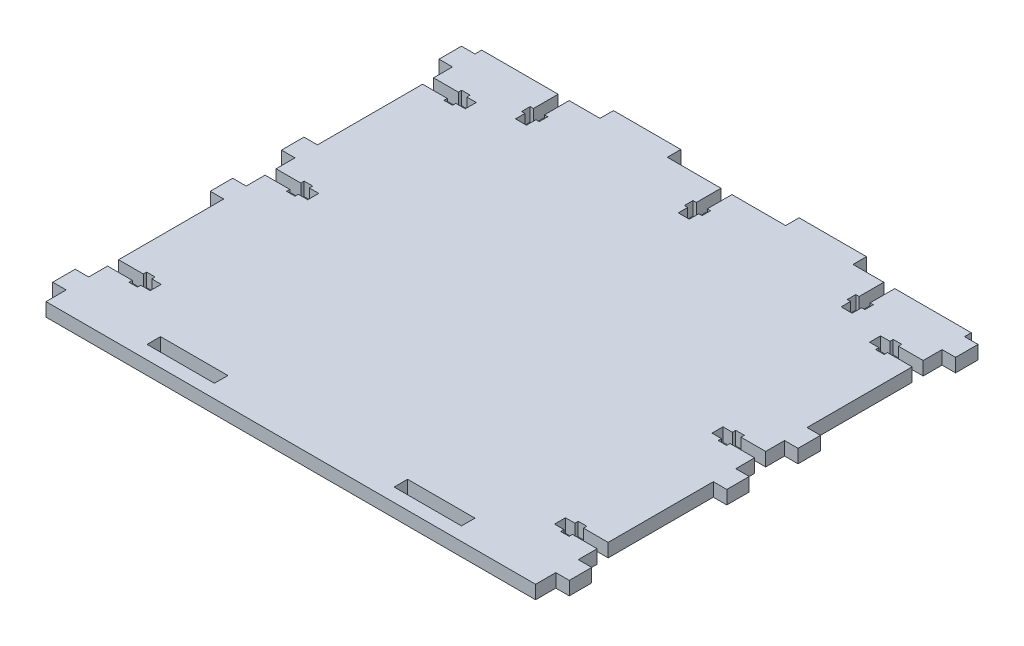
SolidWorks part; units mm, degrees
ref_plane "Спереди" through (0, 0, 0) normal (0, 0, 1) x (1, 0, 0)
ref_plane "Сверху" through (0, 0, 0) normal (0, 1, 0) x (1, 0, 0)
ref_plane "Справа" through (0, 0, 0) normal (1, 0, 0) x (0, 0, -1)
sketch "Эскиз1" plane through (0, 0, 0) normal (0, 1, 0) x (1, 0, 0)
  line L0 (0, 0) -> (0, 50000) construction
  line L1 (0, 0) -> (50000, 0) construction
  line L2 (-44.5, 88.435) -> (44.5, 88.435) construction
  line L3 (-44.5, -88.435) -> (44.5, -88.435) construction
  line L4 (26.3333, 100) -> (26.3333, 94)
  line L5 (115, -100) -> (-115, -100) construction
  line L6 (115, -100) -> (115, 100) construction
  line L7 (115, 100) -> (-115, 100) construction
  line L8 (-115, -100) -> (-115, 100) construction
  line L9 (115, -100) -> (-115, 100) construction
  line L10 (115, 100) -> (-115, -100) construction
  line L11 (26.3333, 94) -> (-26.3333, 94) construction
  line L12 (26.3333, 100) -> (56.3333, 100)
  line L13 (56.3333, 100) -> (56.3333, 94)
  line L14 (56.3333, 94) -> (109, 94) construction
  line L15 (-56.3333, 100) -> (-56.3333, 94)
  line L16 (-26.3333, 100) -> (-56.3333, 100)
  line L17 (-26.3333, 100) -> (-26.3333, 94)
  line L18 (-74.95, 94) -> (-74.95, 83)
  line L19 (109, 20.8625) -> (115, 20.8625)
  line L21 (115, -81) -> (109, -81)
  line L22 (109, -81) -> (109, -72.5875)
  line L23 (109, -20.8625) -> (115, -20.8625)
  line L24 (115, -20.8625) -> (115, -10.8625)
  line L25 (109, 81) -> (109, 20.8625) construction
  line L26 (115, 81) -> (109, 81)
  line L28 (109, -94) -> (-109, -94)
  line L29 (115, -10.8625) -> (109, -10.8625)
  line L30 (109, -29.275) -> (105, -29.275) construction
  line L32 (109, -59.275) -> (105, -59.275) construction
  line L33 (105, -29.275) -> (105, -59.275) construction
  line L34 (109, -10.8625) -> (109, 10.8625) construction
  line L35 (115, 20.8625) -> (115, 10.8625)
  line L36 (115, 10.8625) -> (109, 10.8625)
  line L37 (-26.3333, 94) -> (-2.45, 94)
  line L38 (-2.45, 94) -> (-2.45, 83)
  line L39 (-2.45, 83) -> (-3.925, 83)
  line L40 (-3.925, 83) -> (-3.925, 79.2)
  line L41 (-3.925, 79.2) -> (-2.45, 79.2)
  line L42 (-2.45, 79.2) -> (-2.45, 75)
  line L43 (-2.45, 75) -> (2.45, 75)
  line L44 (26.3333, 94) -> (2.45, 94)
  line L45 (2.45, 79.2) -> (2.45, 75)
  line L46 (3.925, 79.2) -> (2.45, 79.2)
  line L47 (3.925, 83) -> (3.925, 79.2)
  line L48 (2.45, 83) -> (3.925, 83)
  line L49 (2.45, 94) -> (2.45, 83)
  line L50 (56.3333, 94) -> (70.05, 94)
  line L51 (72.5, 109.967) -> (72.5, 64.792) construction
  line L52 (70.05, 94) -> (70.05, 83)
  line L53 (70.05, 83) -> (68.575, 83)
  line L54 (68.575, 83) -> (68.575, 79.2)
  line L55 (68.575, 79.2) -> (70.05, 79.2)
  line L56 (70.05, 79.2) -> (70.05, 75)
  line L57 (70.05, 75) -> (74.95, 75)
  line L59 (74.95, 79.2) -> (74.95, 75)
  line L60 (76.425, 79.2) -> (74.95, 79.2)
  line L61 (76.425, 83) -> (76.425, 79.2)
  line L62 (74.95, 83) -> (76.425, 83)
  line L63 (74.95, 94) -> (74.95, 83)
  line L64 (-74.95, 83) -> (-76.425, 83)
  line L65 (-76.425, 83) -> (-76.425, 79.2)
  line L66 (-76.425, 79.2) -> (-74.95, 79.2)
  line L67 (-74.95, 79.2) -> (-74.95, 75)
  line L68 (-109, 94) -> (-74.95, 94)
  line L69 (-70.05, 75) -> (-74.95, 75)
  line L70 (-70.05, 79.2) -> (-70.05, 75)
  line L71 (-68.575, 79.2) -> (-70.05, 79.2)
  line L72 (-68.575, 83) -> (-68.575, 79.2)
  line L73 (-70.05, 83) -> (-68.575, 83)
  line L74 (-70.05, 94) -> (-70.05, 83)
  line L75 (-56.3333, 94) -> (-70.05, 94)
  line L77 (-115, 81) -> (-109, 81)
  line L78 (109, 81) -> (109, 72.5875)
  line L79 (109, 72.5875) -> (98, 72.5875)
  line L80 (98, 72.5875) -> (98, 74.0625)
  line L81 (98, 74.0625) -> (94.2, 74.0625)
  line L82 (94.2, 74.0625) -> (94.2, 72.5875)
  line L83 (94.2, 72.5875) -> (90, 72.5875)
  line L84 (90, 72.5875) -> (90, 67.6875)
  line L85 (121.1032, 70.1375) -> (81.5914, 70.1375) construction
  line L86 (94.2, 67.6875) -> (90, 67.6875)
  line L87 (94.2, 66.2125) -> (94.2, 67.6875)
  line L88 (98, 66.2125) -> (94.2, 66.2125)
  line L89 (98, 67.6875) -> (98, 66.2125)
  line L90 (109, 67.6875) -> (98, 67.6875)
  line L91 (109, -67.6875) -> (98, -67.6875)
  line L92 (98, -67.6875) -> (98, -66.2125)
  line L93 (98, -66.2125) -> (94.2, -66.2125)
  line L94 (94.2, -66.2125) -> (94.2, -67.6875)
  line L95 (94.2, -67.6875) -> (90, -67.6875)
  line L96 (90, -72.5875) -> (90, -67.6875)
  line L97 (94.2, -72.5875) -> (90, -72.5875)
  line L98 (94.2, -74.0625) -> (94.2, -72.5875)
  line L99 (98, -74.0625) -> (94.2, -74.0625)
  line L100 (98, -72.5875) -> (98, -74.0625)
  line L101 (109, -72.5875) -> (98, -72.5875)
  line L102 (109, -67.6875) -> (109, -20.8625)
  line L103 (109, 67.6875) -> (109, 20.8625)
  line L104 (109, 2.45) -> (98, 2.45)
  line L105 (98, 2.45) -> (98, 3.925)
  line L106 (98, 3.925) -> (94.2, 3.925)
  line L107 (94.2, 3.925) -> (94.2, 2.45)
  line L108 (94.2, 2.45) -> (90, 2.45)
  line L109 (90, 2.45) -> (90, -2.45)
  line L110 (94.2, -2.45) -> (90, -2.45)
  line L111 (94.2, -3.925) -> (94.2, -2.45)
  line L112 (98, -3.925) -> (94.2, -3.925)
  line L113 (98, -2.45) -> (98, -3.925)
  line L114 (109, -2.45) -> (98, -2.45)
  line L115 (109, 2.45) -> (109, 10.8625)
  line L116 (109, -2.45) -> (109, -10.8625)
  line L117 (-109, 81) -> (-109, 72.5875)
  line L118 (-109, -67.6875) -> (-109, -20.8625)
  line L119 (-109, -10.8625) -> (-109, 10.8625) construction
  line L120 (109, -94) -> (109, -91)
  line L121 (-109, -2.45) -> (-109, -10.8625)
  line L122 (-109, 2.45) -> (-109, 10.8625)
  line L123 (-109, -2.45) -> (-98, -2.45)
  line L124 (-98, -2.45) -> (-98, -3.925)
  line L125 (-98, -3.925) -> (-94.2, -3.925)
  line L126 (-94.2, -3.925) -> (-94.2, -2.45)
  line L127 (-94.2, -2.45) -> (-90, -2.45)
  line L128 (-90, 2.45) -> (-90, -2.45)
  line L129 (-94.2, 2.45) -> (-90, 2.45)
  line L130 (-94.2, 3.925) -> (-94.2, 2.45)
  line L131 (-98, 3.925) -> (-94.2, 3.925)
  line L132 (-98, 2.45) -> (-98, 3.925)
  line L133 (-109, 2.45) -> (-98, 2.45)
  line L134 (-109, 67.6875) -> (-109, 20.8625)
  line L135 (-109, -72.5875) -> (-98, -72.5875)
  line L136 (-98, -72.5875) -> (-98, -74.0625)
  line L137 (-98, -74.0625) -> (-94.2, -74.0625)
  line L138 (-94.2, -74.0625) -> (-94.2, -72.5875)
  line L139 (-94.2, -72.5875) -> (-90, -72.5875)
  line L140 (-90, -72.5875) -> (-90, -67.6875)
  line L141 (-94.2, -67.6875) -> (-90, -67.6875)
  line L142 (-94.2, -66.2125) -> (-94.2, -67.6875)
  line L143 (-98, -66.2125) -> (-94.2, -66.2125)
  line L144 (-98, -67.6875) -> (-98, -66.2125)
  line L145 (-109, -67.6875) -> (-98, -67.6875)
  line L146 (-109, 67.6875) -> (-98, 67.6875)
  line L147 (-98, 67.6875) -> (-98, 66.2125)
  line L148 (-98, 66.2125) -> (-94.2, 66.2125)
  line L149 (-94.2, 66.2125) -> (-94.2, 67.6875)
  line L150 (-94.2, 67.6875) -> (-90, 67.6875)
  line L151 (-90, 72.5875) -> (-90, 67.6875)
  line L152 (-94.2, 72.5875) -> (-90, 72.5875)
  line L153 (-94.2, 74.0625) -> (-94.2, 72.5875)
  line L154 (-98, 74.0625) -> (-94.2, 74.0625)
  line L155 (-98, 72.5875) -> (-98, 74.0625)
  line L156 (-109, 72.5875) -> (-98, 72.5875)
  line L157 (-115, 10.8625) -> (-109, 10.8625)
  line L158 (-115, 20.8625) -> (-115, 10.8625)
  line L159 (-115, -10.8625) -> (-109, -10.8625)
  line L160 (-115, -20.8625) -> (-115, -10.8625)
  line L161 (-109, -20.8625) -> (-115, -20.8625)
  line L162 (-109, -81) -> (-109, -72.5875)
  line L163 (-115, -81) -> (-109, -81)
  line L165 (-109, 20.8625) -> (-115, 20.8625)
  line L166 (109, -91) -> (115, -91)
  line L167 (115, -91) -> (115, -81)
  line L168 (109, 94) -> (109, 91)
  line L169 (109, 91) -> (115, 91)
  line L170 (115, 91) -> (115, 81)
  line L171 (109, 94) -> (74.95, 94)
  line L172 (-115, -91) -> (-115, -81)
  line L173 (-109, -91) -> (-115, -91)
  line L174 (-109, -94) -> (-109, -91)
  line L175 (-115, 91) -> (-115, 81)
  line L176 (-109, 91) -> (-115, 91)
  line L177 (-109, 94) -> (-109, 91)
  line L178 (109, -20.8625) -> (109, -29.275) construction
  line L179 (114.9807, 99.9313) -> (90.9807, 99.9313) construction
  line L180 (114.9807, 99.9313) -> (114.9807, 23.9313) construction
  line L181 (114.9807, 23.9313) -> (90.9807, 23.9313) construction
  line L182 (90.9807, 99.9313) -> (90.9807, 23.9313) construction
  line L183 (109, -59.275) -> (109, -67.6875) construction
  circle A0 centre (0, 0) radius 99 construction
  dimension "D1" = 198
  dimension "D2" = 176.87
  dimension "D3" = 200
  dimension "D4" = 30
  dimension "D5" = 6
  dimension "D6" = 230
  dimension "D7" = 6
  dimension "D8" = 3
  dimension "D9" = 4
  dimension "D10" = 30
  dimension "D11" = 4.9
  dimension "D12" = 25
  dimension "D13" = 3.8
  dimension "D14" = 7.85
  dimension "D15" = 17
  dimension "D16" = 10
  dimension "D17" = 10
  dimension "D18" = 76
  dimension "D19" = 24
  dimension "D20" = 72.5
extrude "Бобышка-Вытянуть1" add sketch "Эскиз1" along normal blind 6
sketch "Эскиз2" plane through (0, 6, 0) normal (0, 1, 0) x (1, 0, 0)
  line L0 (0, 0) -> (0, -50000) construction
  line L1 (0, 0) -> (-50000, 0) construction
  line L2 (-109, -94) -> (-109, -100)
  line L3 (-109, -94) -> (109, -94) construction
  line L4 (-109, -100) -> (109, -100)
  line L5 (109, -94) -> (109, -100)
  line L6 (-109, -94) -> (109, -94)
  line L7 (-109, -72.5875) -> (-109, -81) construction
  line L8 (115, -100) -> (-115, -100) construction
extrude "Бобышка-Вытянуть2" add sketch "Эскиз2" against normal up to surface (6 mm away) up to face at (0, 0, -24.5816)
sketch "Эскиз3" [suppressed] plane through (0, 6, 0) normal (0, 1, 0) x (1, 0, 0)
  line L0 (0, 0) -> (0, -50000) construction
  line L1 (0, 0) -> (-50000, 0) construction
  line L14 (60, 4.75) -> (60, 46.25)
  line L15 (50, 56.25) -> (-50, 56.25)
  line L16 (-60, 46.25) -> (-60, 4.75)
  line L17 (-60, 4.75) -> (-77.5, 4.75)
  line L18 (-77.5, 4.75) -> (-77.5, -4.75)
  line L19 (-77.5, -4.75) -> (77.5, -4.75)
  line L20 (77.5, -4.75) -> (77.5, 4.75)
  line L21 (77.5, 4.75) -> (60, 4.75)
  line L22 (60, -4.75) -> (60, 46.25)
  line L23 (50, 56.25) -> (-50, 56.25)
  line L24 (-60, 46.25) -> (-60, -4.75)
  line L27 (-60, -4.75) -> (60, -4.75)
  circle A0 centre (71, -9.25) radius 2.5 construction
  circle A1 centre (71, 50.75) radius 2.5 construction
  arc A2 (60, 46.25) -> (50, 56.25) centre (50, 46.25) ccw
  arc A3 (-50, 56.25) -> (-60, 46.25) centre (-50, 46.25) ccw
  arc A4 (60, 46.25) -> (50, 56.25) centre (50, 46.25) ccw
  arc A5 (-50, 56.25) -> (-60, 46.25) centre (-50, 46.25) ccw
  circle A6 centre (-71, -9.25) radius 2.5 construction
  circle A7 centre (-71, 50.75) radius 2.5 construction
  circle A8 centre (71, -9.25) radius 2.5
  circle A9 centre (71, 50.75) radius 2.5
  circle A10 centre (-71, -9.25) radius 2.5
  circle A11 centre (-71, 50.75) radius 2.5
  dimension "D1" = 0
extrude "Вырез-Вытянуть1" [suppressed] cut sketch "Эскиз3" against normal through all both and the other way through all
sketch "Эскиз4" plane through (0, 0, 0) normal (0, -1, 0) x (1, 0, 0)
  line L0 (-109, -2.45) -> (-109, -19)
  line L1 (-109, -19) -> (109, -19)
  line L2 (-109, -2.45) -> (-250, -2.45)
  line L3 (-250, -2.45) -> (-250, -502.45)
  line L4 (-250, -502.45) -> (250, -502.45)
  line L5 (0, 0) -> (0, -50000) construction
  line L6 (250, -2.45) -> (250, -502.45)
  line L7 (109, -2.45) -> (250, -2.45)
  line L8 (109, -2.45) -> (109, -19)
  line L9 (115, -19) -> (109, -19) construction
  line L10 (98, -2.45) -> (109, -2.45) construction
  dimension "D1" = 500
  dimension "D2" = 500
extrude "Вырез-Вытянуть2" [suppressed] cut sketch "Эскиз4" against normal through all both and the other way through all
sketch "Эскиз5" plane through (0, 6, 0) normal (0, 1, 0) x (1, 0, 0)
  line L0 (-109, 2.45) -> (-109, 14)
  line L1 (-109, 10.8625) -> (-109, 2.45) construction
  line L2 (-109, 14) -> (-78, 14)
  line L3 (-78, 14) -> (-78, 84.5)
  line L4 (-78, 84.5) -> (78, 84.5)
  line L5 (-109, 2.45) -> (-179, 2.45)
  line L6 (-179, 2.45) -> (-179, 164)
  line L7 (-179, 164) -> (179, 164)
  line L8 (0, 0) -> (0, 50000) construction
  line L9 (179, 2.45) -> (179, 164)
  line L10 (109, 2.45) -> (179, 2.45)
  line L11 (78, 14) -> (78, 84.5)
  line L12 (109, 14) -> (78, 14)
  line L13 (109, 2.45) -> (109, 14)
  line L14 (-56.3333, 94) -> (-70.05, 94) construction
  line L15 (-80, 11) -> (-80, 62) construction
  line L16 (0, 0) -> (-50000, 0) construction
  dimension "D1" = 70
  dimension "D2" = 70
  dimension "D3" = 2
  dimension "D4" = 14
  dimension "D5" = 84.5
extrude "Вырез-Вытянуть3" [suppressed] cut sketch "Эскиз5" against normal through all both and the other way through all
sketch "Эскиз6" [suppressed] plane through (0, 6, 0) normal (0, 1, 0) x (1, 0, 0)
  line L1 (-78, 84.5) -> (78, 84.5)
  line L2 (-78, 84.5) -> (-78, 14)
  line L3 (-78, 14) -> (78, 14)
  line L4 (78, 84.5) -> (78, 14)
extrude "Бобышка-Вытянуть3" [suppressed] add sketch "Эскиз6" against normal up to surface (6 mm away)
sketch "Эскиз8" [suppressed] plane through (0, 0, 0) normal (0, -1, 0) x (1, 0, 0)
  circle A0 centre (-101, -15) radius 1.5
  circle A1 centre (-101, -15) radius 2.2 construction
  circle A2 centre (-60.6, -15) radius 1.5
  circle A3 centre (-20.2, -15) radius 1.5
  circle A4 centre (20.2, -15) radius 1.5
  circle A5 centre (60.6, -15) radius 1.5
  circle A6 centre (101, -15) radius 1.5
  circle A7 centre (-60.6, -15) radius 2.2 construction
  dimension "D1" = 3
  dimension "D2" = 6
extrude "Вырез-Вытянуть4" [suppressed] cut sketch "Эскиз8" against normal through all both and the other way through all
fillet "Скругление1" [suppressed] radius 4
sketch "Эскиз9" plane through (0, 6, 0) normal (0, 1, 0) x (1, 0, 0)
  line L0 (0, 0) -> (0, -50000) construction
  line L1 (0, 0) -> (50000, 0) construction
  line L2 (-109, -100) -> (109, -100) construction
  line L3 (-70, -94) -> (-40, -94)
  line L4 (-70, -94) -> (-70, -88)
  line L5 (-70, -88) -> (-40, -88)
  line L6 (-40, -94) -> (-40, -88)
  line L7 (40, -94) -> (40, -88)
  line L8 (70, -88) -> (40, -88)
  line L9 (70, -94) -> (70, -88)
  line L10 (70, -94) -> (40, -94)
  point P15 (-55, -88)
  dimension "D1" = 6
  dimension "D2" = 30
  dimension "D3" = 6
  dimension "D4" = 110
extrude "Вырез-Вытянуть5" cut sketch "Эскиз9" against normal through all both and the other way through all
